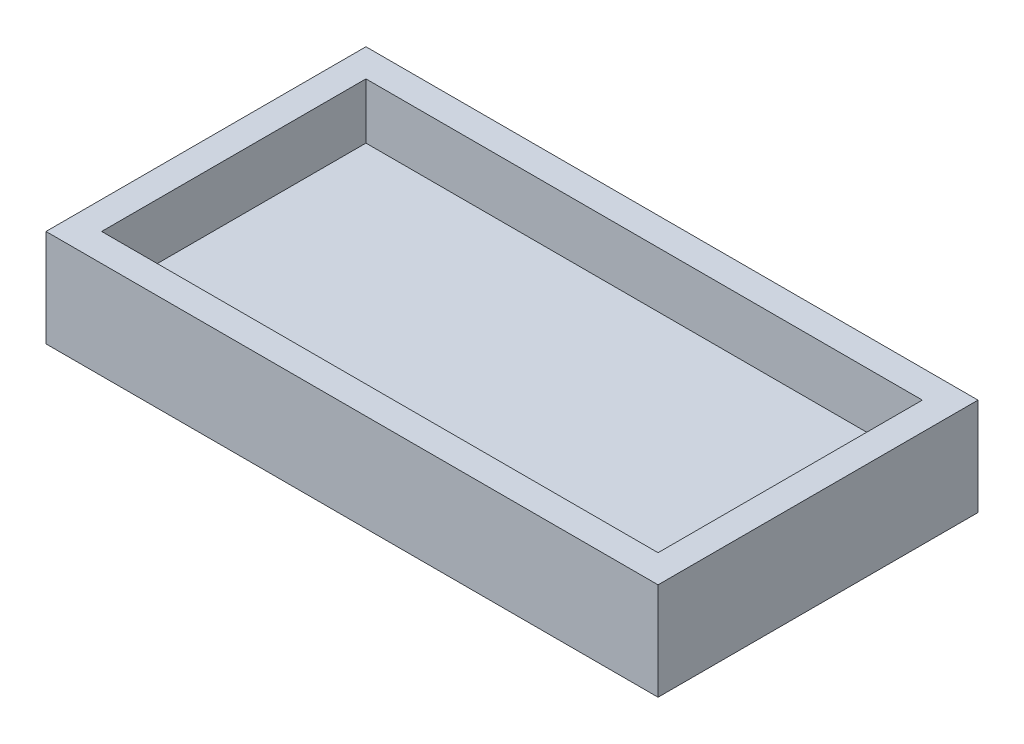
SolidWorks part; units mm, degrees
ref_plane "Front Plane" through (0, 0, 0) normal (0, 0, 1) x (1, 0, 0)
ref_plane "Top Plane" through (0, 0, 0) normal (0, 1, 0) x (1, 0, 0)
ref_plane "Right Plane" through (0, 0, 0) normal (1, 0, 0) x (0, 0, -1)
sketch "Sketch1" plane through (0, 0, 0) normal (0, 1, 0) x (1, 0, 0)
  line L1 (-20, 9.5) -> (20, 9.5)
  line L2 (-20, 9.5) -> (-20, -9.5)
  line L3 (-20, -9.5) -> (20, -9.5)
  line L4 (20, 9.5) -> (20, -9.5)
  line L5 (-20, 9.5) -> (20, -9.5) construction
  line L6 (-20, -9.5) -> (20, 9.5) construction
  point P0 (0, 0)
extrude "Boss-Extrude1" add sketch "Sketch1" along normal blind 3
sketch "Sketch2" plane through (0, 0, 0) normal (0, -1, 0) x (1, 0, 0)
  line L0 (-20, -9.5) -> (-20, 9.5) construction
  line L1 (20, -9.5) -> (-20, -9.5)
  line L2 (20, -9.5) -> (20, 9.5)
  line L3 (20, 9.5) -> (-20, 9.5)
  line L4 (-20, -9.5) -> (-20, 9.5)
  line L9 (22, -11.5) -> (22, 11.5)
  line L14 (22, 11.5) -> (-22, 11.5)
  line L15 (-22, -11.5) -> (-22, 11.5)
  line L16 (22, -11.5) -> (-22, -11.5)
  dimension "D2" = 2
extrude "Boss-Extrude2" add sketch "Sketch2" against normal offset from surface (7 mm away) 4 up to face at (0, 3, 0) offset beyond the face yes
